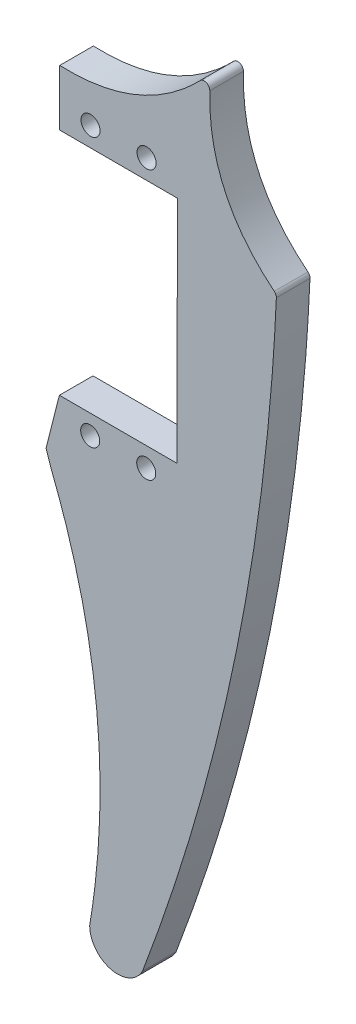
SolidWorks part; units mm, degrees
material "ABS"
ref_plane "Front Plane" through (0, 0, 0) normal (0, 0, 1) x (1, 0, 0)
ref_plane "Top Plane" through (0, 0, 0) normal (0, 1, 0) x (1, 0, 0)
ref_plane "Right Plane" through (0, 0, 0) normal (1, 0, 0) x (0, 0, -1)
sketch "Sketch1" plane through (0, 0, 0) normal (0, 0, 1) x (1, 0, 0)
  line L1 (-25, -73) -> (25, -73)
  line L2 (-25, -73) -> (-25, 73)
  line L3 (-25, 73) -> (25, 73)
  line L4 (25, -73) -> (25, 73)
  line L5 (-25, -73) -> (25, 73) construction
  line L6 (-25, 73) -> (25, -73) construction
  point P0 (0, 0)
  dimension "D1" = 50
  dimension "D2" = 146
extrude "Boss-Extrude1" add sketch "Sketch1" along normal blind 6
sketch "Sketch3" plane through (0, 0, 6) normal (0, 0, 1) x (1, 0, 0)
  line L0 (-18.1577, 62.4611) -> (-18.1698, 52.4611)
  line L1 (-18.1698, 52.4611) -> (2.8301, 52.4355)
  line L2 (2.8301, 52.4355) -> (2.7802, 11.4356)
  line L3 (2.7802, 11.4356) -> (-18.2198, 11.4611)
  line L4 (-18.2198, 11.4611) -> (-20.6029, 2.0952)
  line L5 (-25, 73) -> (25, 73)
  line L6 (25, 73) -> (25, -73)
  line L7 (25, -73) -> (-25, -73)
  line L8 (-25, -73) -> (-25, 73)
  circle A0 centre (-12.724, 7.9545) radius 1.7
  circle A1 centre (-2.724, 7.9423) radius 1.7
  circle A2 centre (-12.6656, 55.9544) radius 1.7
  circle A3 centre (-2.6656, 55.9422) radius 1.7
  arc A4 (6.9003, 72.6534) -> (8.6175, 71.93) centre (7.6179, 71.9569) cw
  arc A5 (20.1233, 46.7018) -> (20.4934, 45.8805) centre (19.4944, 45.9243) cw
  arc A6 (20.4944, 45.9231) -> (20.1233, 46.7018) centre (19.4944, 45.9243) ccw construction
  arc A7 (-12.8163, -67.7955) -> (-3.3861, -70.1197) centre (-7.8163, -67.8016) ccw
  arc A8 (-12.8163, -67.7955) -> (-3.3861, -70.1197) centre (-7.8163, -67.8016) ccw construction
  spline S0 degree 2 poles (8.6175, 71.93) (8.1984, 56.3487) (20.1233, 46.7018) knots 0.080015 0.080015 0.080015 0.985244 0.985244 0.985244 weights 1 1 1 construction
  spline S1 degree 3 poles (-20.6029, 2.0952) (-20.0205, 0.1176) (-18.5975, -3.3343) (-16.9042, -8.2632) (-15.5957, -12.5461) (-14.4561, -16.8104) (-13.503, -20.9757) (-12.4751, -26.3756) (-11.593, -32.6604) (-10.8025, -42.8899) (-11.0088, -54.6421) (-12.1531, -63.8384) (-12.8163, -67.7955) knots 0 0 0 0 0.086646 0.157135 0.219373 0.275195 0.342966 0.399252 0.506628 0.609998 0.831095 1 1 1 1
  spline S2 degree 2 poles (-20.5559, 1.4618) (-6.7301, -31.4908) (-12.8163, -67.7955) knots 0.004655 0.004655 0.004655 1 1 1 weights 1 1 1 construction
  spline S3 degree 3 poles (-3.3861, -70.1197) (-2.2175, -67.0295) (-0.1824, -61.4321) (2.3206, -54.0109) (4.3961, -47.472) (6.0842, -41.8268) (7.7734, -35.8279) (9.3145, -30.0063) (10.8472, -23.7774) (12.2485, -17.634) (13.3818, -12.2462) (14.4459, -6.8132) (15.4509, -1.2735) (16.5413, 5.3978) (17.5258, 12.2275) (18.3183, 18.5775) (18.9682, 24.556) (19.5468, 30.7474) (20.0911, 37.9797) (20.3738, 43.1533) (20.4934, 45.8805) knots 0 0 0 0 0.083335 0.150214 0.197536 0.256374 0.298828 0.354729 0.408267 0.460623 0.51366 0.547132 0.600265 0.655666 0.71763 0.774303 0.817072 0.869314 0.931145 1 1 1 1
  spline S4 degree 2 poles (20.4934, 45.8805) (17.8703, -13.9112) (-3.3861, -70.1197) knots 0.004232 0.004232 0.004232 1 1 1 weights 1 1 1 construction
  spline S5 degree 3 poles (8.6175, 71.93) (8.5907, 70.9316) (8.6162, 68.5087) (8.9751, 65.3342) (9.6754, 62.1669) (10.4078, 59.8785) (11.3756, 57.5671) (12.4767, 55.4209) (13.9857, 53.0738) (15.6991, 50.9092) (17.7271, 48.7578) (19.2236, 47.4296) (20.1233, 46.7018) knots 0 0 0 0 0.104003 0.25221 0.331596 0.441573 0.501853 0.592428 0.69239 0.791956 0.879472 1 1 1 1
  spline S6 degree 3 poles (-18.1577, 62.4611) (-16.5958, 62.4005) (-13.7728, 62.4643) (-9.6976, 63.0746) (-6.3235, 64.0142) (-3.3308, 65.2192) (-0.9448, 66.4543) (1.1131, 67.7452) (3.761, 69.6585) (5.6318, 71.3461) (6.9003, 72.6534) knots 0 0 0 0 0.167942 0.302841 0.441809 0.543311 0.649111 0.730099 0.8042 1 1 1 1
  spline S7 degree 2 poles (-18.1577, 62.4611) (-3.5411, 61.8953) (6.9003, 72.6534) knots 0 0 0 0.915673 0.915673 0.915673 weights 1 1 1 construction
  line M1 (25, -73) -> (25, 73)
  line M2 (25, 73) -> (-25, 73)
  line M3 (-25, 73) -> (-25, -73)
  line M4 (-25, -73) -> (25, -73)
extrude "Cut-Extrude1" cut sketch "Sketch3" against normal through all contours L0 S6 A4 S5 A5 S3 A7 S1 L4 L3 L2 L1 M4 M1 M2 M3 | A0 | A1 | A2 | A3
